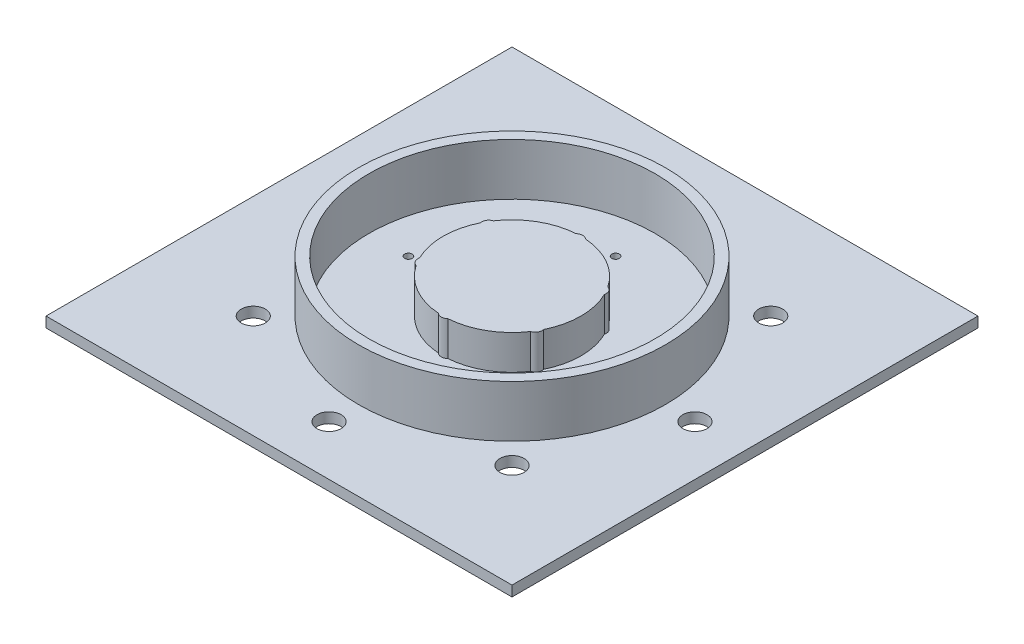
SolidWorks part; units mm, degrees
ref_plane "Front Plane" through (0, 0, 0) normal (0, 0, 1) x (1, 0, 0)
ref_plane "Top Plane" through (0, 0, 0) normal (0, 1, 0) x (1, 0, 0)
ref_plane "Right Plane" through (0, 0, 0) normal (1, 0, 0) x (0, 0, -1)
sketch "Sketch1" plane through (0, 0, 0) normal (0, 1, 0) x (1, 0, 0)
  line L1 (0, 0) -> (135, 0)
  line L2 (0, 0) -> (0, 135)
  line L3 (0, 135) -> (135, 135)
  line L4 (135, 0) -> (135, 135)
  dimension "D1" = 135
  dimension "D2" = 135
extrude "Boss-Extrude1" add sketch "Sketch1" along normal blind 3
sketch "Sketch2" plane through (0, 3, 0) normal (0, 1, 0) x (1, 0, 0)
  line L0 (0, 0) -> (135, 135) construction
  circle A0 centre (67.5, 67.5) radius 20
  arc A1 (66.1254, 87.4527) -> (68.8746, 87.4527) centre (67.5, 86) cw
  arc A2 (66.1254, 87.4527) -> (68.8746, 87.4527) centre (67.5, 67.5) cw
  arc A3 (84.0922, 78.6668) -> (85.4669, 76.2859) centre (83.5215, 76.75) cw
  arc A4 (84.0922, 78.6668) -> (85.4669, 76.2859) centre (67.5, 67.5) cw
  arc A5 (85.4669, 58.7141) -> (84.0922, 56.3332) centre (83.5215, 58.25) cw
  arc A6 (85.4669, 58.7141) -> (84.0922, 56.3332) centre (67.5, 67.5) cw
  arc A7 (68.8746, 47.5473) -> (66.1254, 47.5473) centre (67.5, 49) cw
  arc A8 (68.8746, 47.5473) -> (66.1254, 47.5473) centre (67.5, 67.5) cw
  arc A9 (50.9078, 56.3332) -> (49.5331, 58.7141) centre (51.4785, 58.25) cw
  arc A10 (50.9078, 56.3332) -> (49.5331, 58.7141) centre (67.5, 67.5) cw
  arc A11 (49.5331, 76.2859) -> (50.9078, 78.6668) centre (51.4785, 76.75) cw
  arc A12 (49.5331, 76.2859) -> (50.9078, 78.6668) centre (67.5, 67.5) cw
  point P28 (67.5, 67.5)
  dimension "D1" = 40
  dimension "D2" = 0.5
  dimension "D3" = 2
  dimension "D4" = 6
extrude "Boss-Extrude2" add sketch "Sketch2" along normal blind 10 contours A0 L0 | L0 A0 | A1 A0 | A7 A8 | A9 A10 | A5 A6 | A3 A4 | A11 A12
sketch "Sketch3" plane through (0, 3, 0) normal (0, 1, 0) x (1, 0, 0)
  circle A0 centre (67.5, 67.5) radius 44.45
  circle A1 centre (67.5, 67.5) radius 41.45
  dimension "D1" = 88.9
  dimension "D2" = 3
extrude "Boss-Extrude3" add sketch "Sketch3" along normal blind 15
sketch "Sketch4" plane through (0, 3, 0) normal (0, 1, 0) x (1, 0, 0)
  line L0 (67.5, 67.5) -> (67.5, 97.5) construction
  line L1 (67.5, 67.5) -> (97.5, 67.5) construction
  circle A0 centre (67.5, 97.5) radius 1.1
  circle A1 centre (97.5, 67.5) radius 1.1
  circle A2 centre (67.5, 37.5) radius 1.1
  circle A3 centre (37.5, 67.5) radius 1.1
  point P2 (67.5, 67.5)
  point P3 (0, 0)
  point P5 (61.4544, 37.8054)
  point P6 (0, 0)
  point P15 (97.9956, 68.0039)
  point P16 (0, 0)
  dimension "D1" = 2.2
  dimension "D4" = 90
  dimension "D5" = 30
  dimension "D3" = 4
extrude "Cut-Extrude1" cut sketch "Sketch4" against normal through all both and the other way through all
sketch "Sketch5" plane through (0, 3, 0) normal (0, 1, 0) x (1, 0, 0)
  line L0 (67.5, 67.5) -> (67.5, 120.5) construction
  circle A0 centre (67.5, 120.5) radius 3.5
  circle A1 centre (104.9767, 104.9767) radius 3.5
  circle A2 centre (120.5, 67.5) radius 3.5
  circle A3 centre (104.9767, 30.0233) radius 3.5
  circle A4 centre (67.5, 14.5) radius 3.5
  circle A5 centre (30.0233, 30.0233) radius 3.5
  circle A6 centre (14.5, 67.5) radius 3.5
  circle A7 centre (30.0233, 104.9767) radius 3.5
  point P3 (67.5, 67.5)
  point P4 (67.5, 67.5)
  dimension "D1" = 7
  dimension "D4" = 53
  dimension "D3" = 8
extrude "Cut-Extrude2" cut sketch "Sketch5" against normal through all both and the other way through all
